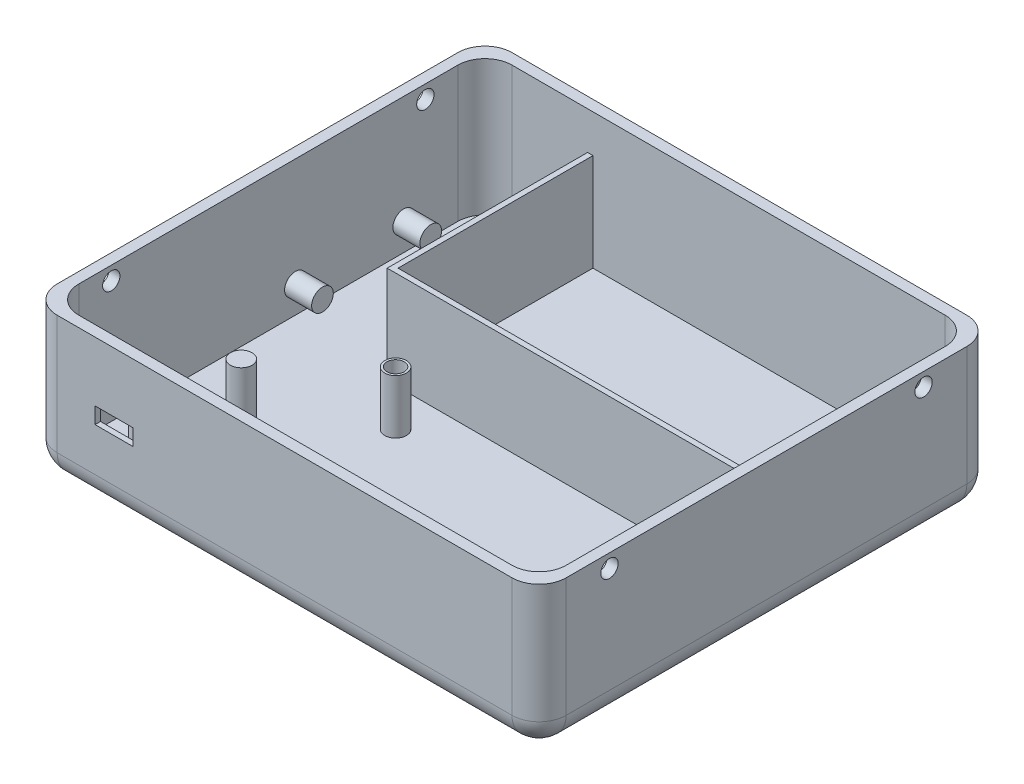
SolidWorks part; units mm, degrees
ref_plane "Front Plane" through (0, 0, 0) normal (0, 0, 1) x (1, 0, 0)
ref_plane "Top Plane" through (0, 0, 0) normal (0, 1, 0) x (1, 0, 0)
ref_plane "Right Plane" through (0, 0, 0) normal (1, 0, 0) x (0, 0, -1)
sketch "Sketch1" plane through (0, 0, 0) normal (0, 1, 0) x (1, 0, 0)
  line L1 (-47, 42) -> (47, 42)
  line L2 (-47, 42) -> (-47, -42)
  line L3 (-47, -42) -> (47, -42)
  line L4 (47, 42) -> (47, -42)
  line L5 (-47, 42) -> (47, -42) construction
  line L6 (-47, -42) -> (47, 42) construction
  point P0 (0, 0)
  dimension "D1" = 84
  dimension "D2" = 94
extrude "Boss-Extrude1" add sketch "Sketch1" along normal blind 27
sketch "Sketch2" plane through (0, 27, 0) normal (0, 1, 0) x (1, 0, 0)
  line L1 (-45, 40) -> (45, 40)
  line L2 (-45, 40) -> (-45, -40)
  line L3 (-45, -40) -> (45, -40)
  line L4 (45, 40) -> (45, -40)
  line L5 (-45, 40) -> (45, -40) construction
  line L6 (-45, -40) -> (45, 40) construction
  point P0 (0, 0)
  dimension "D1" = 80
  dimension "D2" = 90
extrude "Cut-Extrude1" cut sketch "Sketch2" against normal blind 25
fillet "Fillet2" radius 5 8 edges at (47, 13.5, -42) (0, 0, -42) (-47, 13.5, -42) (-47, 0, 0) (-47, 13.5, 42) (47, 0, 0) (0, 0, 42) (47, 13.5, 42)
fillet "Fillet3" radius 5 4 edges at (45, 14.5, -40) (45, 14.5, 40) (-45, 14.5, 40) (-45, 14.5, -40)
sketch "Sketch3" plane through (0, 2, 0) normal (0, 1, 0) x (1, 0, 0)
  line L0 (45, -35) -> (45, 35) construction
  line L3 (-40, -40) -> (40, -40) construction
  line L5 (45, -35) -> (45, 35) construction
  circle A0 centre (33.5, -35) radius 2
  circle A1 centre (33.5, -4) radius 2
  circle A2 centre (-17.5, -4) radius 2
  circle A3 centre (-17.5, -35) radius 2
  dimension "D1" = 4
  dimension "D2" = 4
  dimension "D3" = 4
  dimension "D4" = 4
  dimension "D5" = 11.5
  dimension "D6" = 5
  dimension "D7" = 11.5
  dimension "D8" = 31
  dimension "D9" = 5
  dimension "D10" = 51
  dimension "D11" = 31
  dimension "D12" = 51
extrude "Boss-Extrude2" add sketch "Sketch3" along normal blind 10
sketch "Sketch4" plane through (0, 12, 0) normal (0, 1, 0) x (1, 0, 0)
  circle A0 centre (-17.5, -4) radius 1.6
  circle A1 centre (33.5, -4) radius 1.6
  circle A2 centre (-17.5, -35) radius 1.6
  circle A3 centre (33.5, -35) radius 1.6
  dimension "D1" = 3.2
  dimension "D2" = 3.2
  dimension "D3" = 3.2
  dimension "D4" = 3.2
extrude "Boss-Extrude3" add sketch "Sketch4" against normal blind 10
sketch "Sketch5" plane through (0, 12, 0) normal (0, 1, 0) x (1, 0, 0)
  circle A1 centre (-17.5, -4) radius 1.6
  circle A2 centre (33.5, -4) radius 1.6
  circle A3 centre (-17.5, -35) radius 1.6
  circle A4 centre (33.5, -35) radius 1.6
  dimension "D1" = 3.2
  dimension "D2" = 3.2
  dimension "D3" = 3.2
  dimension "D4" = 3.2
extrude "Cut-Extrude2" cut sketch "Sketch5" against normal blind 10
sketch "Sketch6" plane through (0, 2, 0) normal (0, 1, 0) x (1, 0, 0)
  line L0 (-40, -40) -> (40, -40) construction
  line L1 (-45, 35) -> (-45, -35) construction
  line L2 (-45, 35) -> (-45, -35) construction
  circle A0 centre (-33, -35) radius 2
  circle A2 centre (-33, -17) radius 2
  dimension "D1" = 4
  dimension "D2" = 12
  dimension "D3" = 4
  dimension "D4" = 12
  dimension "D5" = 5
  dimension "D6" = 18
extrude "Boss-Extrude4" add sketch "Sketch6" along normal blind 10
sketch "Sketch12" plane through (0, 2, 0) normal (0, 1, 0) x (1, 0, 0)
  line L0 (40, 40) -> (-40, 40) construction
  line L1 (-26.0484, 40) -> (40.9516, 40)
  line L2 (-26.0484, 40) -> (-26.0484, 3)
  line L3 (-26.0484, 3) -> (40.9516, 3)
  line L4 (40.9516, 40) -> (40.9516, 3)
  line L5 (45, -35) -> (45, 35) construction
  dimension "D1" = 37
  dimension "D2" = 67
  dimension "D3" = 71.0484
extrude "Boss-Extrude5" add sketch "Sketch12" along normal blind 18
sketch "Sketch13" plane through (0, 20, 0) normal (0, 1, 0) x (1, 0, 0)
  line L0 (40, 40) -> (-26.0484, 40) construction
  line L1 (-25.0484, 40) -> (39.9516, 40)
  line L2 (-25.0484, 40) -> (-25.0484, 4)
  line L3 (-25.0484, 4) -> (39.9516, 4)
  line L4 (39.9516, 40) -> (39.9516, 4)
  line L5 (-26.0484, 40) -> (-26.0484, 3) construction
  line L6 (40.9516, 3) -> (40.9516, 39.9086) construction
  line L7 (-26.0484, 3) -> (40.9516, 3) construction
  dimension "D1" = 1
  dimension "D2" = 1
  dimension "D3" = 1
extrude "Cut-Extrude4" cut sketch "Sketch13" against normal blind 18
sketch "Sketch14" plane through (0, 0, 40) normal (0, 0, -1) x (-1, 0, 0)
  line L0 (40, 2) -> (40, 27) construction
  line L1 (40, 16) -> (23, 16)
  line L2 (40, 16) -> (40, 12)
  line L3 (40, 12) -> (23, 12)
  line L4 (23, 16) -> (23, 12)
  line L5 (40, 2) -> (-40, 2) construction
  dimension "D1" = 17
  dimension "D2" = 4
  dimension "D3" = 10
extrude "Cut-Extrude5" cut sketch "Sketch14" against normal blind 1
sketch "Sketch16" plane through (0, 0, 41) normal (0, 0, -1) x (-1, 0, 0)
  line L0 (23, 12) -> (40, 12) construction
  line L9 (28, 16) -> (35, 16)
  line L10 (28, 16) -> (28, 13)
  line L11 (28, 13) -> (35, 13)
  line L12 (35, 16) -> (35, 13)
  line L13 (28, 16) -> (35, 13) construction
  line L14 (28, 13) -> (35, 16) construction
  line L15 (40, 12) -> (40, 16) construction
  point P0 (31.5, 14.5)
  dimension "D1" = 7
  dimension "D2" = 3
  dimension "D3" = 1
  dimension "D4" = 8.5
extrude "Cut-Extrude6" cut sketch "Sketch16" against normal blind 1
sketch "Sketch17" plane through (-45, 0, 0) normal (1, 0, 0) x (0, 0, -1)
  line L0 (35, 2) -> (-35, 2) construction
  line L1 (35, 2) -> (35, 27) construction
  circle A0 centre (25, 7) radius 2
  circle A1 centre (5, 7) radius 2
  dimension "D1" = 4
  dimension "D2" = 4
  dimension "D3" = 5
  dimension "D4" = 5
  dimension "D5" = 10
  dimension "D6" = 20
extrude "Boss-Extrude6" add sketch "Sketch17" along normal blind 5
sketch "Sketch18" plane through (-45, 0, 0) normal (1, 0, 0) x (0, 0, -1)
  line L0 (35, 27) -> (-35, 27) construction
  line L1 (-35, 27) -> (-35, 2) construction
  line L2 (35, 2) -> (35, 27) construction
  circle A0 centre (29, 24.5) radius 1.6
  circle A1 centre (-29, 24.5) radius 1.6
  dimension "D1" = 3.2
  dimension "D2" = 3.2
  dimension "D3" = 2.5
  dimension "D4" = 6
  dimension "D5" = 2.5
  dimension "D6" = 6
extrude "Cut-Extrude7" cut sketch "Sketch18" against normal blind 2
sketch "Sketch19" plane through (45, 0, 0) normal (-1, 0, 0) x (0, 0, 1)
  line L0 (35, 27) -> (-35, 27) construction
  line L1 (-35, 27) -> (-35, 2) construction
  line L2 (35, 2) -> (35, 27) construction
  circle A0 centre (-29, 24.5) radius 1.6
  circle A1 centre (29, 24.5) radius 1.6
  dimension "D1" = 3.2
  dimension "D2" = 3.2
  dimension "D3" = 2.5
  dimension "D4" = 6
  dimension "D5" = 2.5
  dimension "D6" = 6
extrude "Cut-Extrude8" cut sketch "Sketch19" against normal blind 2
